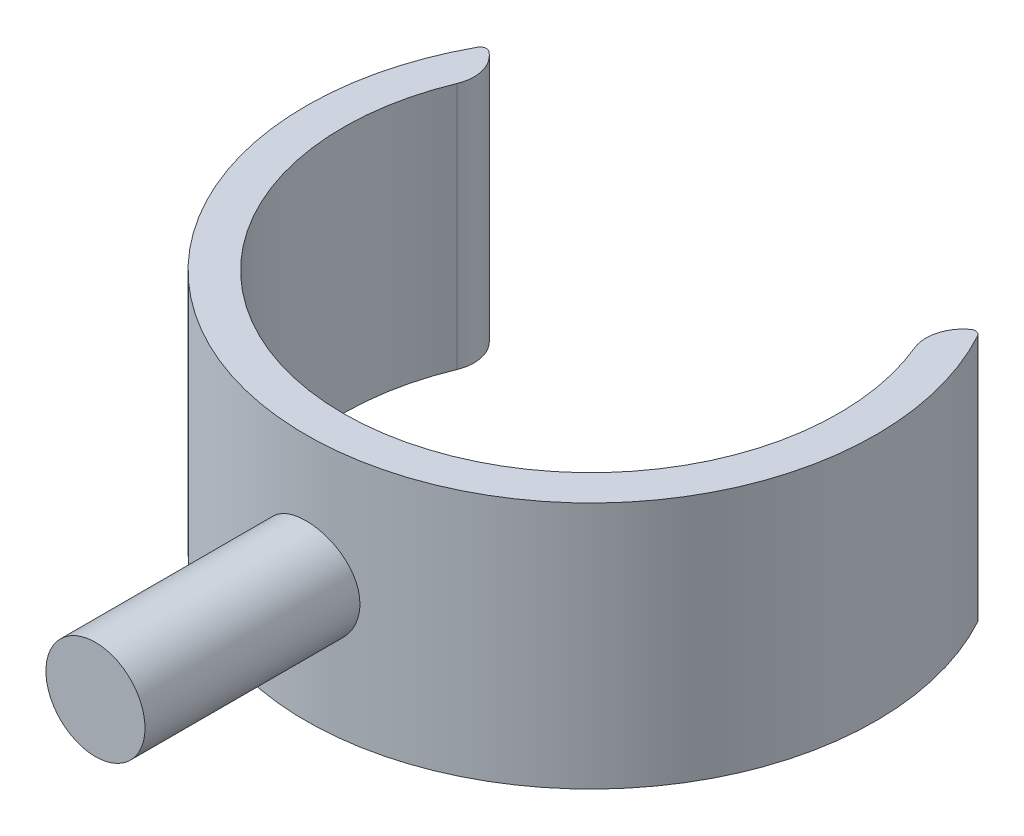
SolidWorks part; units mm, degrees
ref_plane "Alzado" through (0, 0, 0) normal (0, 0, 1) x (1, 0, 0)
ref_plane "Planta" through (0, 0, 0) normal (0, 1, 0) x (1, 0, 0)
ref_plane "Vista lateral" through (0, 0, 0) normal (1, 0, 0) x (0, 0, -1)
sketch "Croquis1" plane through (0, 0, 0) normal (0, 1, 0) x (1, 0, 0)
  line L0 (0, 0) -> (0, 40) construction
  line L1 (0, 0) -> (19.9186, 11.5)
  line L2 (0, 0) -> (-19.9186, 11.5)
  arc A0 (-19.9186, 11.5) -> (19.9186, 11.5) centre (0, 0) ccw
  arc A1 (-17.3205, 10) -> (17.3205, 10) centre (0, 0) ccw
  circle A3 centre (0, 0) radius 20 construction
  circle A4 centre (0, 0) radius 23 construction
  point P3 (38.2522, 11.6949)
  point P8 (37, 0)
  dimension "D1" = 46
  dimension "D3" = 60
  dimension "D2" = 3
extrude "Extruir1" add sketch "Croquis1" along normal blind 20 contours A1 L2 A0 L1
sketch "Croquis2" plane through (0, 0, 0) normal (0, 0, 1) x (1, 0, 0)
  line L0 (0, 0) -> (0, 20) construction
  line L1 (23, 20) -> (-23, 20) construction
  circle A0 centre (0, 10) radius 4
  dimension "D1" = 8
extrude "Extruir2" add sketch "Croquis2" against normal up to surface (17.3505 mm away) from offset 40
fillet "Redondeo1" radius 3 2 edges at (-17.3205, 10, -10) (17.3205, 10, -10)
fillet "Redondeo2" radius 0.5 2 edges at (19.9186, 10, -11.5) (-19.9186, 10, -11.5)
